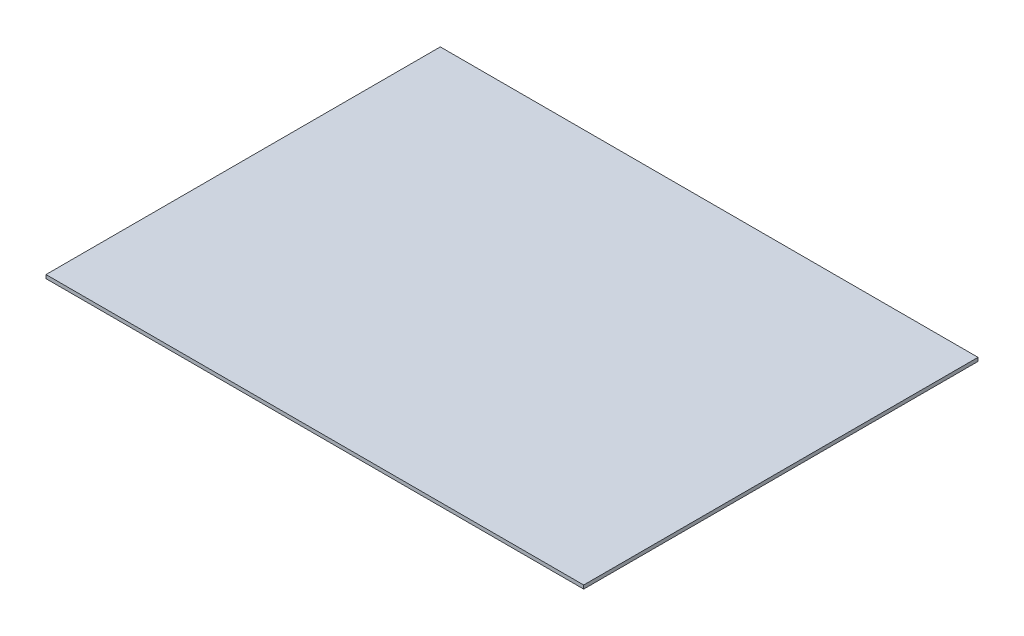
SolidWorks part; units mm, degrees
ref_plane "Front Plane" through (0, 0, 0) normal (0, 0, 1) x (1, 0, 0)
ref_plane "Top Plane" through (0, 0, 0) normal (0, 1, 0) x (1, 0, 0)
ref_plane "Right Plane" through (0, 0, 0) normal (1, 0, 0) x (0, 0, -1)
sketch "Sketch1" plane through (0, 0, 0) normal (0, 1, 0) x (1, 0, 0)
  line L1 (-150, -110) -> (150, -110)
  line L2 (-150, -110) -> (-150, 110)
  line L3 (-150, 110) -> (150, 110)
  line L4 (150, -110) -> (150, 110)
  line L5 (-150, -110) -> (150, 110) construction
  line L6 (-150, 110) -> (150, -110) construction
  point P0 (0, 0)
  dimension "D1" = 300
  dimension "D2" = 220
extrude "Boss-Extrude1" add sketch "Sketch1" along normal blind 2
